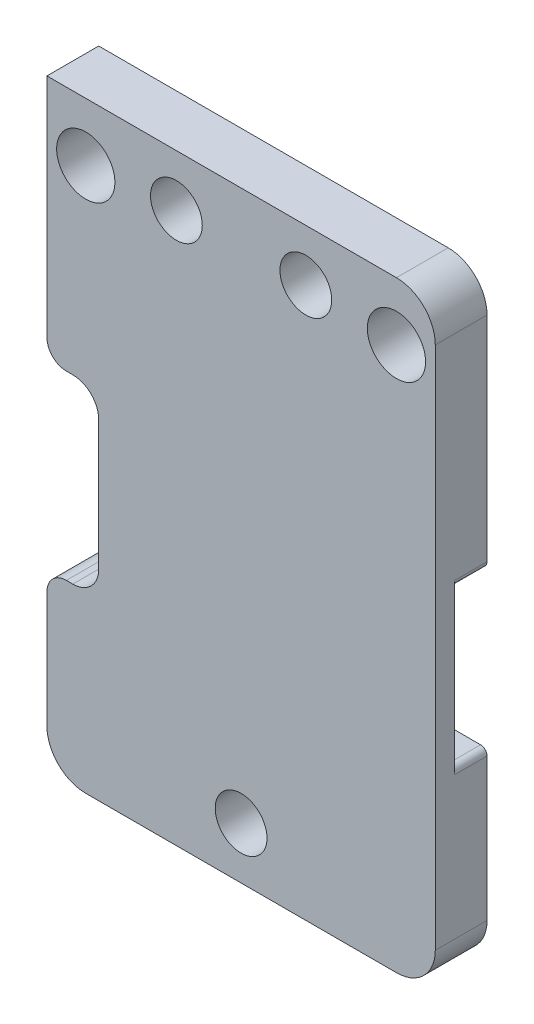
SolidWorks part; units mm, degrees
ref_plane "Front Plane" through (0, 0, 0) normal (0, 0, 1) x (1, 0, 0)
ref_plane "Top Plane" through (0, 0, 0) normal (0, 1, 0) x (1, 0, 0)
ref_plane "Right Plane" through (0, 0, 0) normal (1, 0, 0) x (0, 0, -1)
sketch "Sketch1" plane through (0, 0, 0) normal (0, 0, 1) x (1, 0, 0)
  line L0 (0, 27.5) -> (0, 46.5)
  line L1 (0, 0) -> (30, 0)
  line L2 (0, 0) -> (0, 13.5)
  line L3 (27, 42) -> (3, 42) construction
  line L4 (30, 0) -> (30, 16)
  line L5 (0, 27.5) -> (4, 27.5)
  line L6 (30, 25) -> (30, 46.5)
  line L7 (0, 13.5) -> (4, 13.5)
  line L8 (12, 26) -> (12, 15) construction
  line L9 (30, 25) -> (24, 25) construction
  line L10 (4, 27.5) -> (4, 26)
  line L11 (30, 16) -> (24, 16) construction
  line L12 (24, 25) -> (24, 16) construction
  line L13 (4, 26) -> (12, 26) construction
  line L14 (12, 15) -> (4, 15) construction
  line L15 (4, 15) -> (4, 13.5)
  line L16 (20, 42.5) -> (10, 42.5) construction
  line L17 (30, 25) -> (30, 16)
  line L18 (0, 27.5) -> (0, 13.5) construction
  line L19 (4, 26) -> (4, 15)
  line L22 (0, 46.5) -> (30, 46.5)
  circle A0 centre (20, 42.5) radius 2
  circle A1 centre (15, 4) radius 2
  circle A2 centre (10, 42.5) radius 2
  circle A3 centre (3, 42) radius 2.25
  circle A4 centre (27, 42) radius 2.25
  point P0 (15, 46.5)
  point P1 (15, 42.5)
  point P13 (24, 20.5)
  point P14 (12, 20.5)
  point P17 (0, 20.5)
  point P27 (15, 42)
  dimension "D6" = 46.5
  dimension "D11" = 10
  dimension "D16" = 12
  dimension "D2" = 4
  dimension "D12" = 4.5
  dimension "D1" = 30
  dimension "D3" = 9
  dimension "D4" = 20.5
  dimension "D5" = 14
  dimension "D7" = 4
  dimension "D8" = 4
  dimension "D9" = 6
  dimension "D10" = 11
  dimension "D13" = 24
  dimension "D14" = 4
  dimension "D15" = 4.5
extrude "Boss-Extrude1" add sketch "Sketch1" along normal blind 4
fillet "Fillet2" radius 1.5 2 edges at (0, 13.5, 2) (0, 27.5, 2)
fillet "Fillet3" radius 2 2 edges at (4, 27.5, 2) (4, 13.5, 2)
fillet "Fillet5" radius 3 3 edges at (30, 0, 2) (0, 0, 2) (30, 46.5, 2)
sketch "Sketch2" plane through (0, 0, 0) normal (0, 0, -1) x (-1, 0, 0)
  line L0 (-26, 32.5) -> (-4, 32.5) construction
  line L1 (-26, 34.5) -> (-18.4641, 34.5)
  line L2 (-26, 30.5) -> (-4, 30.5)
  line L3 (-26, 8.5) -> (-4, 8.5) construction
  line L4 (-26, 10.5) -> (-4, 10.5)
  line L5 (-17.5359, 6.5) -> (-12.4641, 6.5)
  line L6 (-11.5359, 34.5) -> (-4, 34.5)
  line L8 (-4, 25.5) -> (-4, 15.5) construction
  line L9 (-5.5359, 6.5) -> (-4, 6.5)
  line L10 (-26, 6.5) -> (-24.4641, 6.5)
  line L11 (-30, 36.5) -> (0, 36.5) construction
  line L12 (-30, 3) -> (-30, 43.5) construction
  line L13 (0, 46.5) -> (0, 29) construction
  line L14 (-15, 34.5) -> (-15, 6.5) construction
  arc A0 (-26, 34.5) -> (-26, 30.5) centre (-26, 32.5) ccw
  arc A1 (-4, 30.5) -> (-4, 34.5) centre (-4, 32.5) ccw
  arc A2 (-26, 10.5) -> (-26, 6.5) centre (-26, 8.5) ccw
  arc A3 (-4, 6.5) -> (-4, 10.5) centre (-4, 8.5) ccw
  arc A4 (-16.7321, 35.5) -> (-13.2679, 35.5) centre (-15, 34.5) cw
  arc A5 (-13.2679, 35.5) -> (-11.5359, 34.5) centre (-11.5359, 36.5) ccw
  arc A6 (-16.7321, 35.5) -> (-18.4641, 34.5) centre (-18.4641, 36.5) cw
  arc A7 (-10.7321, 5.5) -> (-7.2679, 5.5) centre (-9, 6.5) ccw
  arc A8 (-19.2679, 5.5) -> (-22.7321, 5.5) centre (-21, 6.5) cw
  arc A9 (-19.2679, 5.5) -> (-17.5359, 6.5) centre (-17.5359, 4.5) cw
  arc A10 (-12.4641, 6.5) -> (-10.7321, 5.5) centre (-12.4641, 4.5) cw
  arc A11 (-7.2679, 5.5) -> (-5.5359, 6.5) centre (-5.5359, 4.5) cw
  arc A12 (-22.7321, 5.5) -> (-24.4641, 6.5) centre (-24.4641, 4.5) ccw
  point P2 (-15, 32.5)
  point P7 (-15, 7.9021)
  point P14 (-4, 20.5)
  point P41 (-15, 6.5)
  point P45 (-15, 36.5)
  point P47 (-15, 8.5)
  dimension "D3" = 2
  dimension "D5" = 2
  dimension "D7" = 2
  dimension "D1" = 12
  dimension "D2" = 12
  dimension "D4" = 22
  dimension "D6" = 12
extrude "Boss-Extrude2" add sketch "Sketch2" along normal blind 1
sketch "Sketch3" plane through (0, 0, 0) normal (0, 0, -1) x (-1, 0, 0)
  line L0 (-4, 25.5) -> (-4, 15.5) construction
  line L1 (2.3332, 27) -> (-12.5, 27)
  line L2 (2.3332, 27) -> (2.3332, 14)
  line L3 (2.3332, 14) -> (-12.5, 14)
  line L4 (-30, 3) -> (-30, 43.5) construction
  line L5 (-13.618, 26.5) -> (-30, 26.5)
  line L6 (-13.618, 26.5) -> (-12.5, 27)
  line L7 (-13.5, 14.5) -> (-30, 14.5)
  line L8 (-30, 26.5) -> (-30, 14.5)
  line L9 (-12.5, 14) -> (-13.5, 14.5)
  point P4 (-30, 20.5)
  point P8 (2.3332, 20.5)
  point P9 (-4, 20.5)
  dimension "D1" = 8.5
  dimension "D2" = 12
  dimension "D3" = 13
  dimension "D4" = 9.5
extrude "Cut-Extrude1" cut sketch "Sketch3" against normal blind 2.5
fillet "Fillet6" radius 0.5 4 edges at (3.3229, 27, 1.25) (3.3229, 14, 1.25) (30, 14.5, 1.25) (30, 26.5, 1.25)
